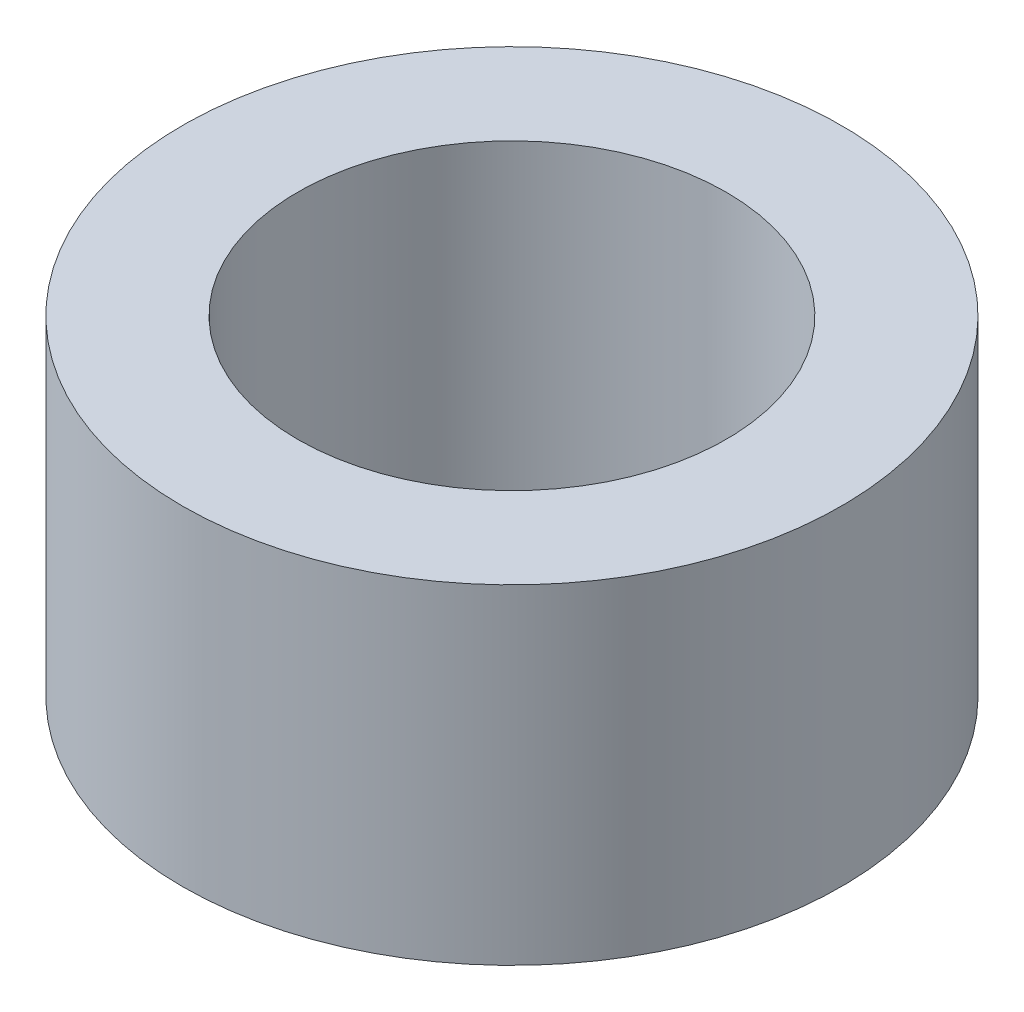
SolidWorks part; units mm, degrees
ref_plane "Front Plane" through (0, 0, 0) normal (0, 0, 1) x (1, 0, 0)
ref_plane "Top Plane" through (0, 0, 0) normal (0, 1, 0) x (1, 0, 0)
ref_plane "Right Plane" through (0, 0, 0) normal (1, 0, 0) x (0, 0, -1)
sketch "Sketch1" plane through (0, 0, 0) normal (0, 1, 0) x (1, 0, 0)
  circle A0 centre (0, 0) radius 3.25
  circle A1 centre (0, 0) radius 5
  dimension "D1" = 6.5
  dimension "D2" = 10
extrude "Boss-Extrude1" add sketch "Sketch1" along normal blind 5
